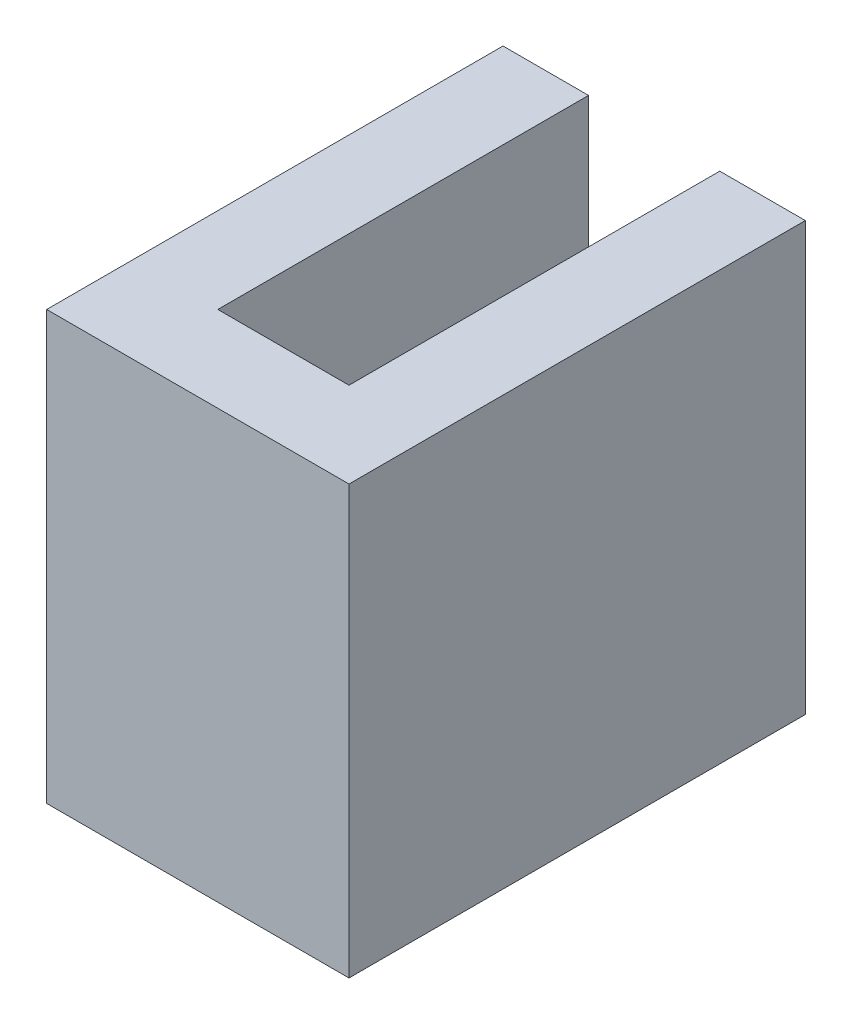
SolidWorks part; units mm, degrees
ref_plane "Front Plane" through (0, 0, 0) normal (0, 0, 1) x (1, 0, 0)
ref_plane "Top Plane" through (0, 0, 0) normal (0, 1, 0) x (1, 0, 0)
ref_plane "Right Plane" through (0, 0, 0) normal (1, 0, 0) x (0, 0, -1)
sketch "Sketch1" plane through (0, 0, 0) normal (0, 1, 0) x (1, 0, 0)
  line L0 (0, 0) -> (0, 16)
  line L1 (0, 16) -> (3, 16)
  line L2 (3, 16) -> (3, 3)
  line L3 (3, 3) -> (7.6, 3)
  line L4 (7.6, 3) -> (7.6, 16)
  line L5 (7.6, 16) -> (10.6, 16)
  line L6 (10.6, 16) -> (10.6, 0)
  line L7 (10.6, 0) -> (0, 0)
  point P9 (7.6, 9.5)
  dimension "D1" = 4.6
  dimension "D2" = 3
  dimension "D3" = 3
  dimension "D4" = 13
  dimension "D5" = 3
extrude "Boss-Extrude1" add sketch "Sketch1" along normal blind 15
